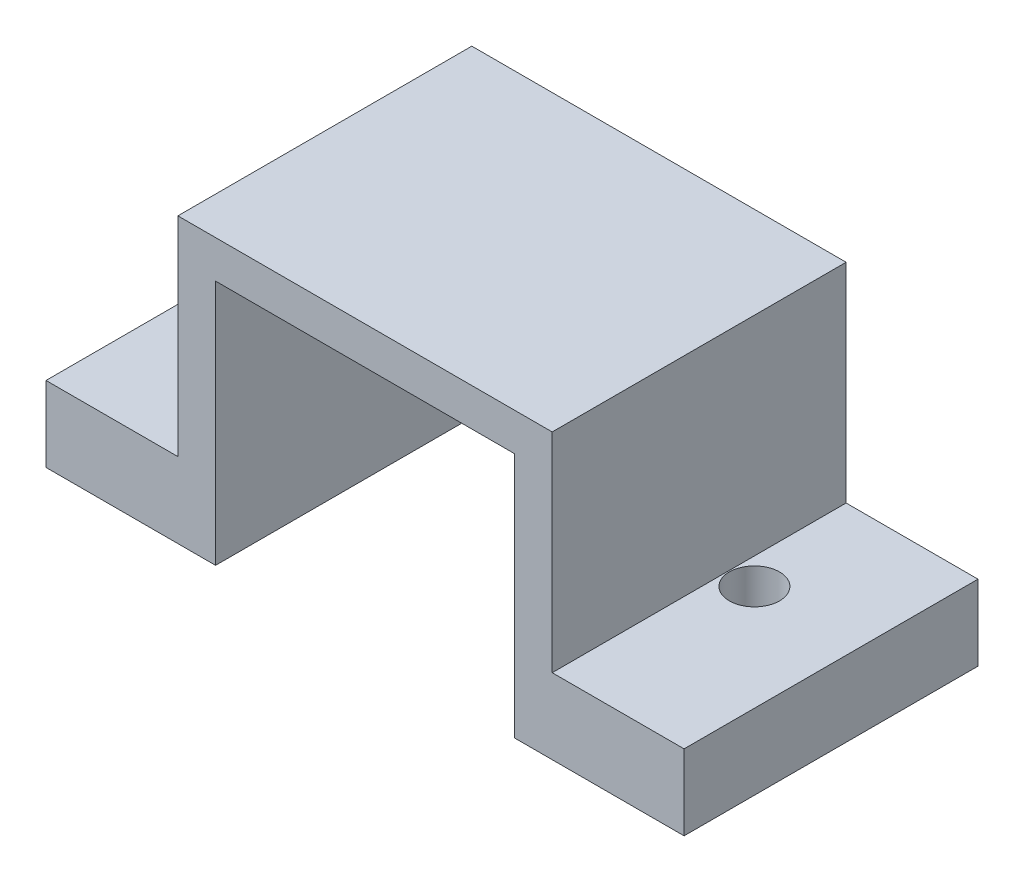
SolidWorks part; units mm, degrees
ref_plane "Alzado" through (0, 0, 0) normal (0, 0, 1) x (1, 0, 0)
ref_plane "Planta" through (0, 0, 0) normal (0, 1, 0) x (1, 0, 0)
ref_plane "Vista lateral" through (0, 0, 0) normal (1, 0, 0) x (0, 0, -1)
sketch "Croquis1" plane through (0, 0, 0) normal (0, 0, 1) x (1, 0, 0)
  line L1 (0, 0) -> (25.4, 0)
  line L2 (0, 0) -> (0, 11.3)
  line L3 (0, 11.3) -> (25.4, 11.3)
  line L4 (25.4, 0) -> (25.4, 11.3)
  dimension "D1" = 25.4
  dimension "D2" = 11.3
extrude "Saliente-Extruir1" add sketch "Croquis1" along normal blind 11.7
sketch "Croquis2" plane through (0, 11.3, 0) normal (0, 1, 0) x (1, 0, 0)
  line L0 (25.4, -11.7) -> (0, -11.7) construction
  line L1 (0, 0) -> (5.25, 0)
  line L2 (0, 0) -> (0, -11.7)
  line L3 (0, -11.7) -> (5.25, -11.7)
  line L4 (5.25, 0) -> (5.25, -11.7)
  line L6 (25.4, 0) -> (20.15, 0)
  line L7 (25.4, 0) -> (25.4, -11.7)
  line L8 (25.4, -11.7) -> (20.15, -11.7)
  line L9 (20.15, 0) -> (20.15, -11.7)
  dimension "D1" = 5.25
  dimension "D2" = 5.25
extrude "Cortar-Extruir1" cut sketch "Croquis2" against normal blind 8.3
sketch "Croquis3" plane through (0, 0, 11.7) normal (0, 0, 1) x (1, 0, 0)
  line L0 (0, 0) -> (25.4, 0) construction
  line L1 (6.75, 9.8) -> (18.65, 9.8)
  line L2 (6.75, 9.8) -> (6.75, 0)
  line L3 (6.75, 0) -> (18.65, 0)
  line L4 (18.65, 9.8) -> (18.65, 0)
  line L5 (20.15, 11.3) -> (5.25, 11.3) construction
  line L6 (5.25, 3) -> (5.25, 11.3) construction
  line L7 (20.15, 3) -> (20.15, 11.3) construction
  dimension "D1" = 1.5
  dimension "D2" = 1.5
  dimension "D3" = 1.5
extrude "Cortar-Extruir2" cut sketch "Croquis3" against normal through all
sketch "Croquis4" plane through (0, 3, 0) normal (0, 1, 0) x (1, 0, 0)
  line L0 (20.15, -11.7) -> (25.4, -11.7) construction
  line L1 (0, -11.7) -> (5.25, -11.7) construction
  line L2 (5.25, -11.7) -> (5.25, 0) construction
  circle A0 centre (21.2, -4.7) radius 1
  circle A1 centre (4.2, -4.7) radius 1
  dimension "D1" = 2
  dimension "D3" = 2
  dimension "D6" = 1.05
  dimension "D2" = 7
  dimension "D4" = 7
  dimension "D5" = 17
extrude "Cortar-Extruir3" cut sketch "Croquis4" against normal through all
